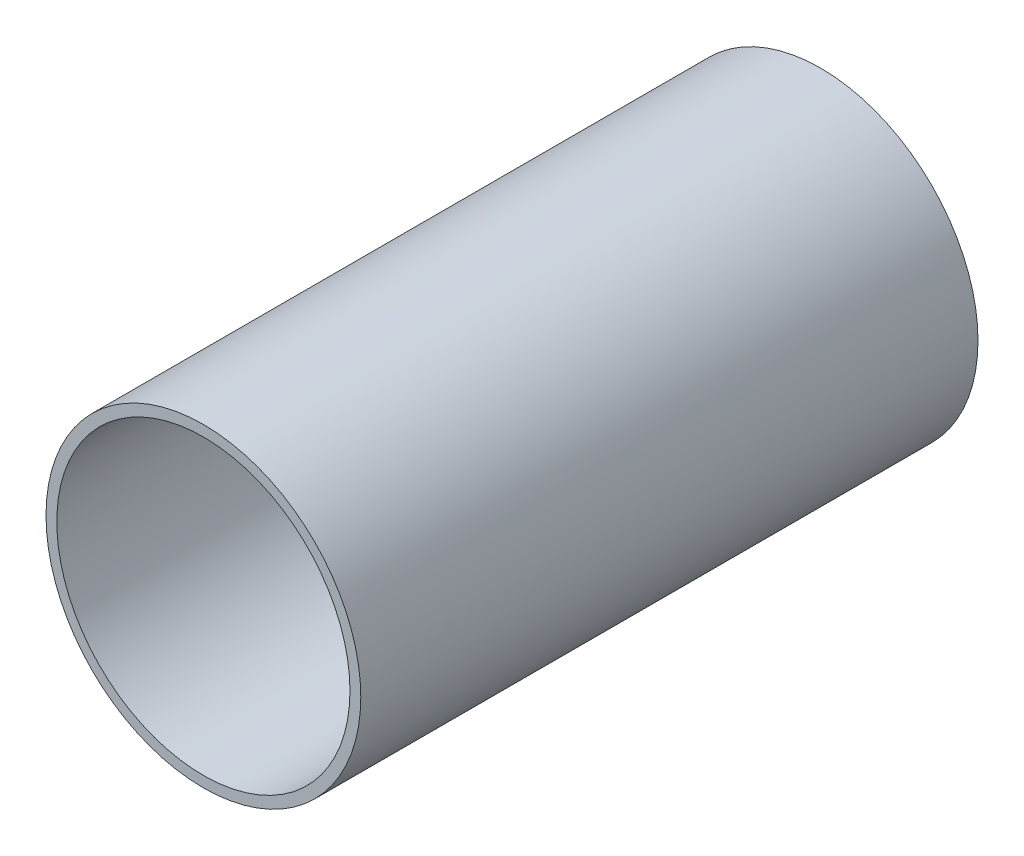
SolidWorks part; units mm, degrees
ref_plane "Front Plane" through (0, 0, 0) normal (0, 0, 1) x (1, 0, 0)
ref_plane "Top Plane" through (0, 0, 0) normal (0, 1, 0) x (1, 0, 0)
ref_plane "Right Plane" through (0, 0, 0) normal (1, 0, 0) x (0, 0, -1)
sketch "Sketch1" plane through (0, 0, 0) normal (0, 0, 1) x (1, 0, 0)
  circle A0 centre (0, 0) radius 2.375
  circle A1 centre (0, 0) radius 2.55
  dimension "D1" = 4.75
  dimension "D2" = 5.1
extrude "Boss-Extrude1" add sketch "Sketch1" along normal blind 10
